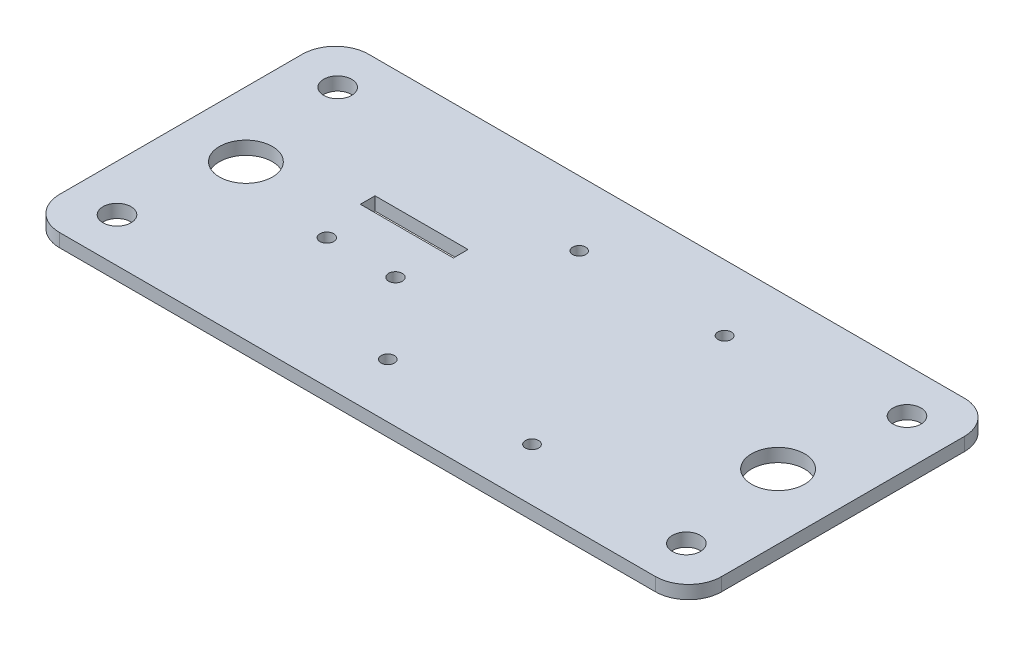
SolidWorks part; units mm, degrees
ref_plane "Front" through (0, 0, 0) normal (0, 0, 1) x (1, 0, 0)
ref_plane "Top" through (0, 0, 0) normal (0, 1, 0) x (1, 0, 0)
ref_plane "Right" through (0, 0, 0) normal (1, 0, 0) x (0, 0, -1)
sketch "Esboço2" plane through (0, 0, 0) normal (0, 1, 0) x (1, 0, 0)
  line L0 (57.0976, 26.6331) -> (57.0976, 42.3811) construction
  line L1 (0, 0) -> (150, 0)
  line L2 (0, 0) -> (0, 70)
  line L3 (0, 70) -> (150, 70)
  line L4 (150, 0) -> (150, 70)
  line L5 (36.0212, 42.9423) -> (57.0976, 42.9423)
  line L6 (36.0212, 42.9423) -> (36.0212, 39.6213)
  line L7 (36.0212, 39.6213) -> (57.0976, 39.6213)
  line L8 (57.0976, 42.9423) -> (57.0976, 39.6213)
  circle A0 centre (103.0826, 55.0826) radius 1.5054
  circle A1 centre (69.5599, 12.3002) radius 1.4985
  circle A2 centre (69.9544, 55.2794) radius 1.4744
  circle A3 centre (102.5702, 11.9687) radius 1.5
  circle A4 centre (38.7651, 29.2684) radius 1.5558
  circle A5 centre (54.3226, 29.2684) radius 1.5558
extrude "Ressalto-extrusão1" add sketch "Esboço2" along normal blind 3
sketch "Esboço4" plane through (0, 3, 0) normal (0, 1, 0) x (1, 0, 0)
  line L0 (0, 70) -> (10.5, 70)
  line L1 (150, 70) -> (0, 70) construction
  line L2 (10.5, 70) -> (10.5, 60)
  line L3 (150, 70) -> (139.5, 70)
  line L4 (139.5, 70) -> (139.5, 60)
  line L5 (10.5, 0) -> (10.5, 10)
  line L6 (0, 0) -> (150, 0) construction
  line L7 (139.5, 0) -> (139.5, 10)
  circle A0 centre (10.5, 60) radius 3.175
  circle A1 centre (139.5, 60) radius 3.175
  circle A2 centre (139.5, 10) radius 3.175
  circle A3 centre (10.5, 10) radius 3.175
  dimension "D1" = 2
  dimension "D3" = 50
  dimension "D4" = 129
  dimension "D2" = 2
extrude "Corte-extrusão1" cut sketch "Esboço4" against normal blind 3
fillet "Filete1" radius 7.5 4 edges at (0, 1.5, 0) (150, 1.5, 0) (150, 1.5, -70) (0, 1.5, -70)
sketch "Esboço8" plane through (0, 3, 0) normal (0, 1, 0) x (1, 0, 0)
  circle A0 centre (14.7075, 35) radius 6
  circle A1 centre (135.2925, 35) radius 6
extrude "Corte-extrusão3" cut sketch "Esboço8" against normal blind 10
sketch "Esboço10" plane through (0, 0, 0) normal (0, -1, 0) x (-1, 0, 0)
